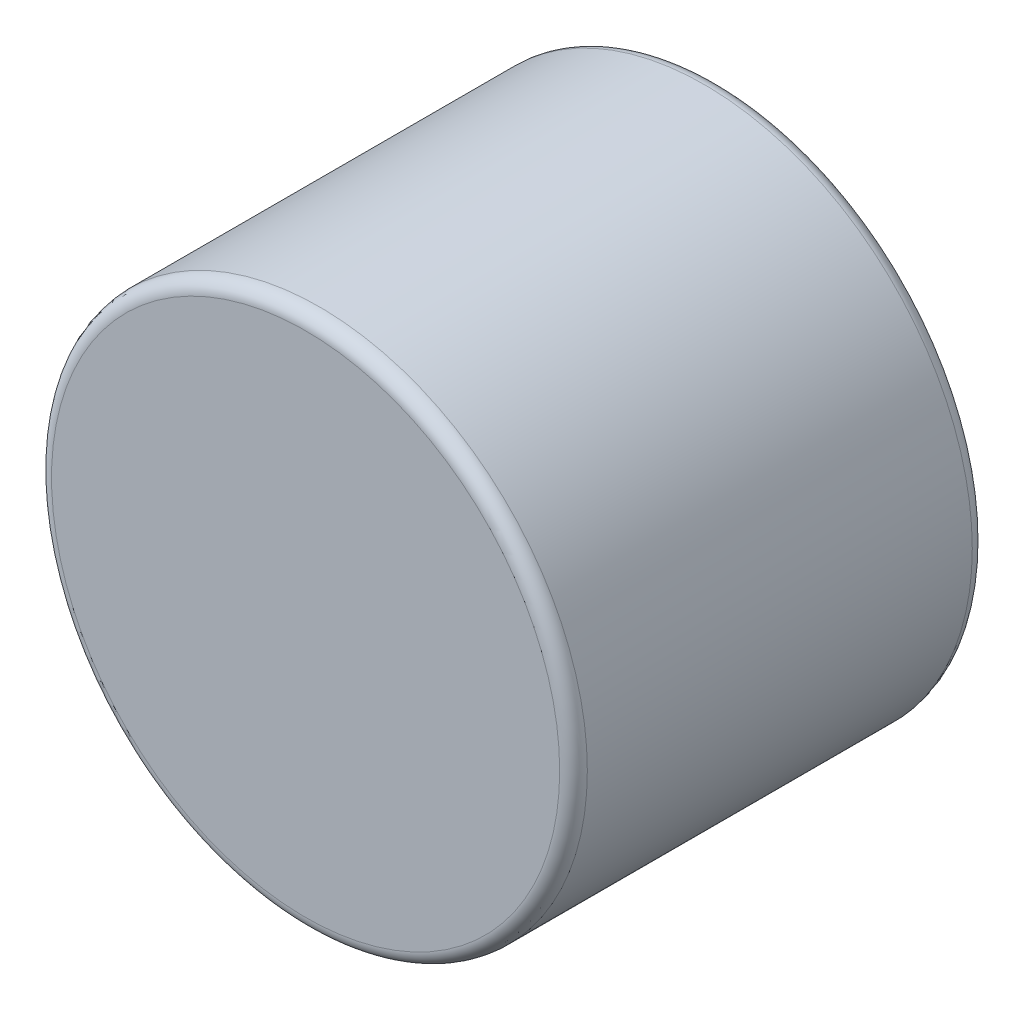
SolidWorks part; units mm, degrees
ref_plane "Front Plane" through (0, 0, 0) normal (0, 0, 1) x (1, 0, 0)
ref_plane "Top Plane" through (0, 0, 0) normal (0, 1, 0) x (1, 0, 0)
ref_plane "Right Plane" through (0, 0, 0) normal (1, 0, 0) x (0, 0, -1)
sketch "Sketch1" plane through (0, 0, 0) normal (0, 0, 1) x (1, 0, 0)
  circle A0 centre (0, 0) radius 49.2125
  dimension "D1" = 98.425
extrude "Boss-Extrude1" add sketch "Sketch1" along normal blind 75.7936
fillet "Fillet1" radius 2.54 2 edges at (49.2125, 0, 0) (49.2125, 0, 75.7936)
sketch "Sketch2" plane through (0, 0, 0) normal (0, 1, 0) x (1, 0, 0)
  line L0 (0, 0) -> (0, -73.2536) construction
  line L1 (49.2125, -73.2536) -> (-49.2125, -73.2536) construction
